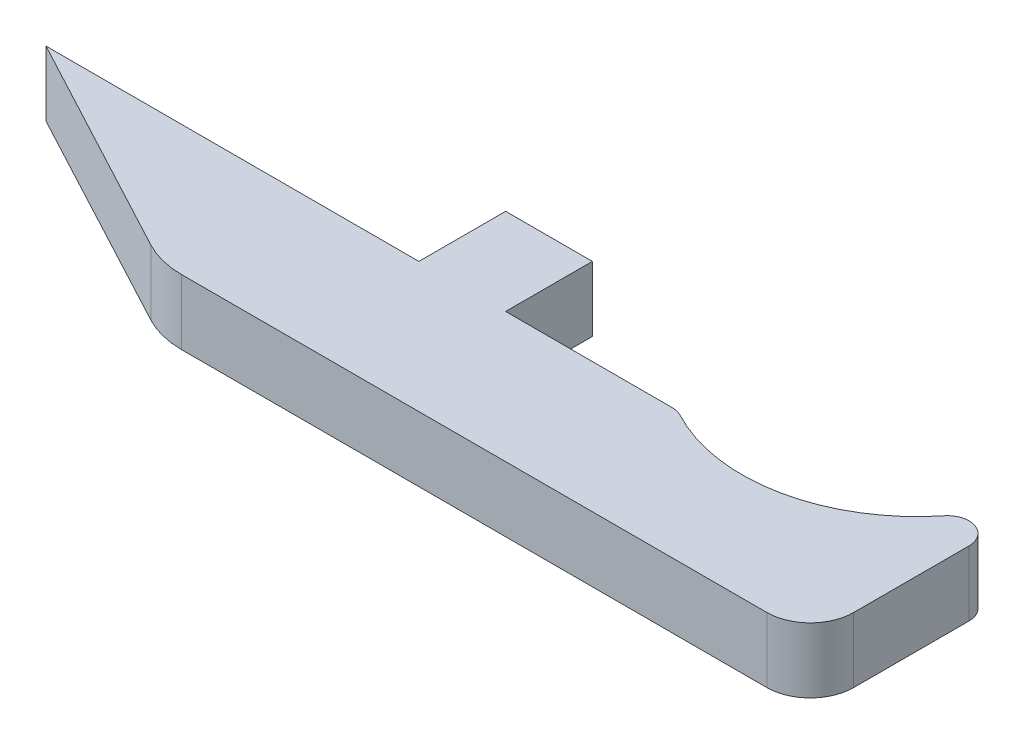
SolidWorks part; units mm, degrees
material "AISI 4130 Steel, annealed at 865C"
ref_plane "X-Y Datum" through (0, 0, 0) normal (0, 0, 1) x (1, 0, 0)
ref_plane "X-Z Datum" through (0, 0, 0) normal (0, 1, 0) x (1, 0, 0)
ref_plane "Y-Z Datum" through (0, 0, 0) normal (1, 0, 0) x (0, 0, -1)
sketch "Sketch1" plane through (0, 0, 0) normal (0, 1, 0) x (1, 0, 0)
  line L0 (58.9432, -32.1114) -> (58.9432, -30.7971) construction
  line L1 (58.9432, -42.5794) -> (3.2156, -42.5794)
  line L2 (58.9432, -42.5794) -> (58.9432, -31.4542)
  line L3 (24.1452, -52.1044) -> (71.7702, -52.1044)
  line L4 (71.7702, -31.4542) -> (71.7702, -52.1044)
  line L5 (6.2845, -42.5794) -> (24.1452, -52.1044)
  line L8 (33.5895, -42.5667) -> (3.1095, -42.5667) construction
  line L9 (33.5895, -42.5667) -> (3.1095, -42.5667)
  circle A0 centre (58.9432, -31.4542) radius 12.827
  circle A1 centre (58.9432, -31.4542) radius 12.7
  circle A2 centre (58.9432, -31.4542) radius 12.7 construction
  point P6 (59.0296, 16.4596)
  point P7 (59.0296, 3.7596)
  point P9 (8.1581, -7.1976)
  point P15 (73.4897, -5.945)
  point P16 (28.392, 24.4431)
  point P18 (0, 0)
  point P19 (58.3065, 3.4802)
  point P21 (3.3033, -7.6323)
  point P22 (4.103, -7.645)
  dimension "D3" = 25.654
  dimension "D5" = 9.525
  dimension "D1" = 55.7276
  dimension "D2" = 11.1252
  dimension "D4" = 3.175
  dimension "D6" = 47.625
extrude "Boss-Extrude1" add sketch "Sketch1" along normal blind 4.7625
fillet "Fillet1" radius 1.5875 2 edges at (52.5587, 2.3813, 42.5794) (71.7702, 2.3813, 31.4542)
fillet "Fillet2" radius 6.35 1 edges at (24.1452, 2.3813, 52.1044)
fillet "Fillet3" radius 3.175 1 edges at (71.7702, 2.3813, 52.1044)
sketch "Sketch2" plane through (0, 0, 42.5794) normal (0, 0, -1) x (-1, 0, 0)
  line L0 (-52.1488, 4.7625) -> (-6.2845, 4.7625) construction
  line L1 (-39.9395, 4.7625) -> (-33.5895, 4.7625)
  line L2 (-39.9395, 4.7625) -> (-39.9395, 0)
  line L3 (-39.9395, 0) -> (-33.5895, 0)
  line L4 (-33.5895, 4.7625) -> (-33.5895, 0)
  line L5 (-52.1488, 0) -> (-6.2845, 0) construction
  line L6 (-6.2845, 4.7625) -> (-6.2845, 0) construction
  dimension "D1" = 27.305
  dimension "D2" = 6.35
extrude "Boss-Extrude2" add sketch "Sketch2" along normal blind 6.35
